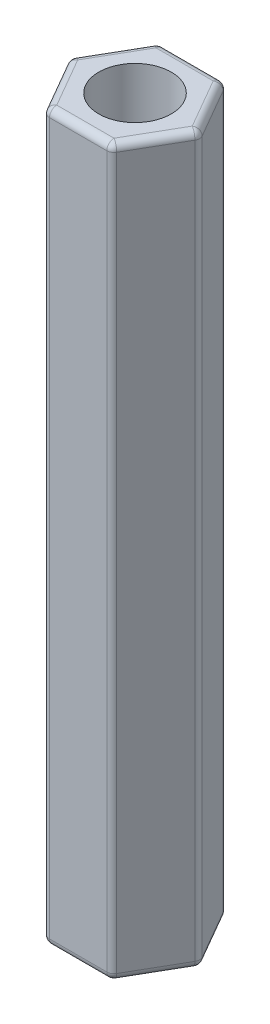
SolidWorks part; units mm, degrees
ref_plane "前视基准面" through (0, 0, 0) normal (0, 0, 1) x (1, 0, 0)
ref_plane "上视基准面" through (0, 0, 0) normal (0, 1, 0) x (1, 0, 0)
ref_plane "右视基准面" through (0, 0, 0) normal (1, 0, 0) x (0, 0, -1)
sketch "草图1" plane through (0, 0, 0) normal (0, 1, 0) x (1, 0, 0)
  line L1 (2.7135, 0) -> (1.3568, 2.35)
  line L2 (1.3568, 2.35) -> (-1.3568, 2.35)
  line L3 (-1.3568, 2.35) -> (-2.7135, 0)
  line L4 (-2.7135, 0) -> (-1.3568, -2.35)
  line L5 (-1.3568, -2.35) -> (1.3568, -2.35)
  line L6 (1.3568, -2.35) -> (2.7135, 0)
  circle A0 centre (0, 0) radius 2.35 construction
  circle A1 centre (0, 0) radius 1.5
  dimension "D1" = 4.7
extrude "凸台-拉伸1" add sketch "草图1" along normal blind 30
fillet "圆角1" radius 0.3 18 edges at (2.7135, 15, 0) (1.3568, 15, -2.35) (-1.3568, 15, -2.35) (-2.7135, 15, 0) (-1.3568, 15, 2.35) (1.3568, 15, 2.35) (0, 30, 2.35) (-2.0352, 30, 1.175) (-2.0352, 30, -1.175) (0, 30, -2.35) (2.0352, 30, -1.175) (2.0352, 30, 1.175) (0, 0, 2.35) (-2.0352, 0, 1.175) (-2.0352, 0, -1.175) (0, 0, -2.35) (2.0352, 0, -1.175) (2.0352, 0, 1.175)
